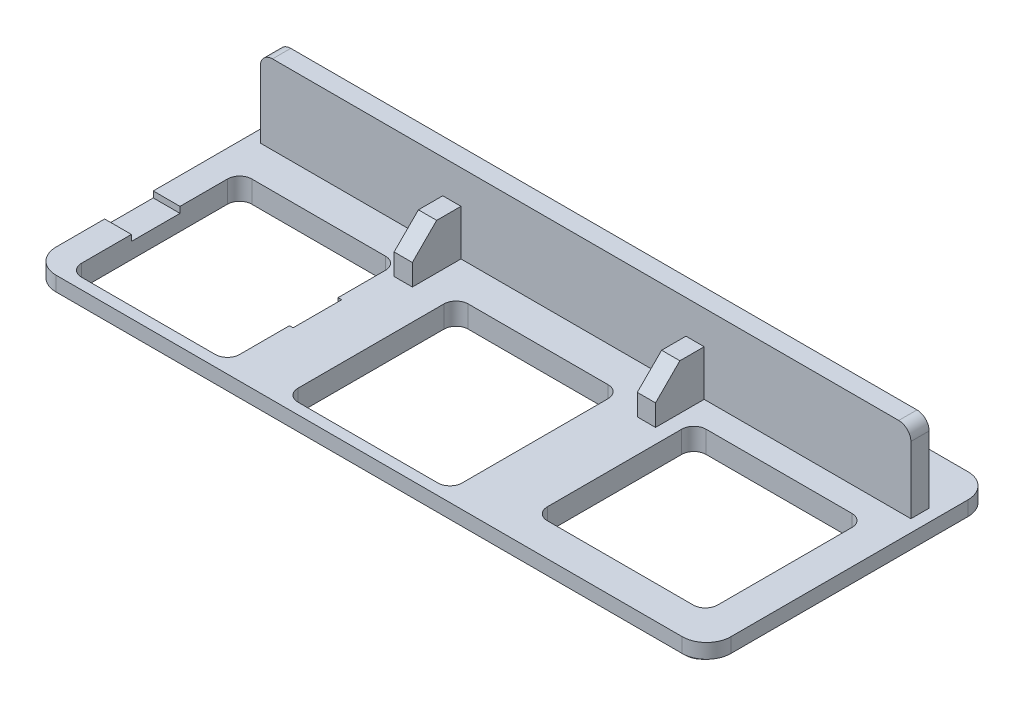
SolidWorks part; units mm, degrees
ref_plane "前视基准面" through (0, 0, 0) normal (0, 0, 1) x (1, 0, 0)
ref_plane "上视基准面" through (0, 0, 0) normal (0, 1, 0) x (1, 0, 0)
ref_plane "右视基准面" through (0, 0, 0) normal (1, 0, 0) x (0, 0, -1)
sketch "草图1" plane through (0, 0, 0) normal (0, 1, 0) x (1, 0, 0)
  line L1 (-27.75, 11.75) -> (27.75, 11.75)
  line L2 (-27.75, 11.75) -> (-27.75, -11.75)
  line L3 (-27.75, -11.75) -> (27.75, -11.75)
  line L4 (27.75, 11.75) -> (27.75, -11.75)
  line L5 (-27.75, 11.75) -> (27.75, -11.75) construction
  line L6 (-27.75, -11.75) -> (27.75, 11.75) construction
  point P0 (0, 0)
  dimension "D1" = 23.5
  dimension "D2" = 55.5
extrude "凸台-拉伸1" add sketch "草图1" along normal blind 1.2
fillet "圆角1" radius 2 4 edges at (-27.75, 0.6, 11.75) (27.75, 0.6, 11.75) (-27.75, 0.6, -11.75) (27.75, 0.6, -11.75)
sketch "草图2" plane through (0, 0, 0) normal (0, -1, 0) x (1, 0, 0)
  line L0 (-27.75, -9.75) -> (-27.75, 9.75) construction
  line L1 (-26.85, 11.15) -> (26.85, 11.15)
  line L2 (-26.85, 11.15) -> (-26.85, -11.15)
  line L3 (-26.85, -11.15) -> (26.85, -11.15)
  line L4 (26.85, 11.15) -> (26.85, -11.15)
  line L5 (27.75, 9.75) -> (27.75, -9.75) construction
  line L6 (-25.75, 11.75) -> (25.75, 11.75) construction
  line L7 (25.75, -11.75) -> (-25.75, -11.75) construction
  dimension "D1" = 0.9
  dimension "D2" = 0.9
  dimension "D3" = 0.6
  dimension "D4" = 0.6
extrude "凸台-拉伸2" add sketch "草图2" along normal blind 0.6
sketch "草图3" plane through (0, -0.6, 0) normal (0, -1, 0) x (1, 0, 0)
  line L1 (-25.55, 10.85) -> (-12.55, 10.85)
  line L2 (-25.55, 10.85) -> (-25.55, -3.15)
  line L3 (-25.55, -3.15) -> (-12.55, -3.15)
  line L4 (-12.55, 10.85) -> (-12.55, -3.15)
  line L5 (-7.75, 10.85) -> (5.75, 10.85)
  line L6 (-7.75, 10.85) -> (-7.75, -3.15)
  line L7 (-7.75, -3.15) -> (5.75, -3.15)
  line L8 (5.75, 10.85) -> (5.75, -3.15)
  line L9 (10.95, 9.0414) -> (24.95, 9.0414)
  line L10 (10.95, 9.0414) -> (10.95, -4.0086)
  line L11 (10.95, -4.0086) -> (24.95, -4.0086)
  line L12 (24.95, 9.0414) -> (24.95, -4.0086)
  line L15 (-27.75, -9.75) -> (-27.75, 9.75) construction
  line L16 (-25.75, 11.75) -> (25.75, 11.75) construction
  line L17 (27.75, 9.75) -> (27.75, -9.75) construction
  dimension "D1" = 13
  dimension "D2" = 13.5
  dimension "D3" = 14
  dimension "D4" = 2.2
  dimension "D5" = 0.9
  dimension "D6" = 20
  dimension "D7" = 13.05
  dimension "D8" = 2.8
  dimension "D10" = 14
extrude "切除-拉伸1" cut sketch "草图3" against normal blind 3
fillet "圆角2" radius 1 12 edges at (-25.55, 0.3, 10.85) (-12.55, 0.3, 10.85) (-7.75, 0.3, 10.85) (5.75, 0.3, 10.85) (24.95, 0.3, 9.0414) (10.95, 0.3, 9.0414) (24.95, 0.3, -4.0086) (10.95, 0.3, -4.0086) (5.75, 0.3, -3.15) (-7.75, 0.3, -3.15) (-12.55, 0.3, -3.15) (-25.55, 0.3, -3.15)
sketch "草图4" plane through (0, 1.2, 0) normal (0, 1, 0) x (1, 0, 0)
  line L0 (-27.75, 9.75) -> (-27.75, -9.75) construction
  line L1 (-12.25, -5.75) -> (-27.75, -5.75)
  line L2 (-12.25, -5.75) -> (-12.25, -1.7526)
  line L3 (-12.25, -1.7526) -> (-27.75, -1.7526)
  line L4 (-27.75, -5.75) -> (-27.75, -1.7526)
  line L5 (-25.75, -11.75) -> (25.75, -11.75) construction
  dimension "D1" = 6
  dimension "D2" = 3.9974
  dimension "D3" = 15.5
extrude "切除-拉伸2" cut sketch "草图4" against normal blind 0.5
sketch "草图5" plane through (0, 1.2, 0) normal (0, 1, 0) x (1, 0, 0)
  line L1 (26.75, 6.0546) -> (-26.75, 6.0546)
  line L2 (26.75, 6.0546) -> (26.75, 7.5546)
  line L3 (26.75, 7.5546) -> (-26.75, 7.5546)
  line L4 (-26.75, 6.0546) -> (-26.75, 7.5546)
  line L6 (-27.75, 9.75) -> (-27.75, -1.7526) construction
  line L7 (27.75, -9.75) -> (27.75, 9.75) construction
  line L8 (25.75, 11.75) -> (-25.75, 11.75) construction
  dimension "D1" = 1.5
  dimension "D2" = 1
  dimension "D3" = 1
  dimension "D4" = 4.1954
extrude "凸台-拉伸3" add sketch "草图5" along normal blind 6.5
fillet "圆角3" radius 1 2 edges at (-26.75, 7.7, -6.8046) (26.75, 7.7, -6.8046)
sketch "草图6" plane through (0, 1.2, 0) normal (0, 1, 0) x (1, 0, 0)
  line L0 (-26.75, 6.0546) -> (26.75, 6.0546) construction
  line L1 (9.75, 6.0546) -> (8.25, 6.0546)
  line L2 (9.75, 6.0546) -> (9.75, 2.0546)
  line L3 (9.75, 2.0546) -> (8.25, 2.0546)
  line L4 (8.25, 6.0546) -> (8.25, 2.0546)
  line L5 (27.75, -9.75) -> (27.75, 9.75) construction
  line L6 (-10.25, 6.0546) -> (-11.75, 6.0546)
  line L7 (-10.25, 6.0546) -> (-10.25, 2.0546)
  line L8 (-10.25, 2.0546) -> (-11.75, 2.0546)
  line L9 (-11.75, 6.0546) -> (-11.75, 2.0546)
  line L10 (-27.75, -5.75) -> (-27.75, -9.75) construction
  dimension "D1" = 4
  dimension "D2" = 1.5
  dimension "D3" = 18
  dimension "D4" = 16
extrude "凸台-拉伸4" add sketch "草图6" along normal blind 3.75
chamfer "倒角1" distance 2 angle 45 2 edges at (-11, 4.95, -2.0546) (9, 4.95, -2.0546)
fillet "圆角4" radius 1.5 4 edges at (-26.85, -0.3, -11.15) (26.85, -0.3, -11.15) (26.85, -0.3, 11.15) (-26.85, -0.3, 11.15)
